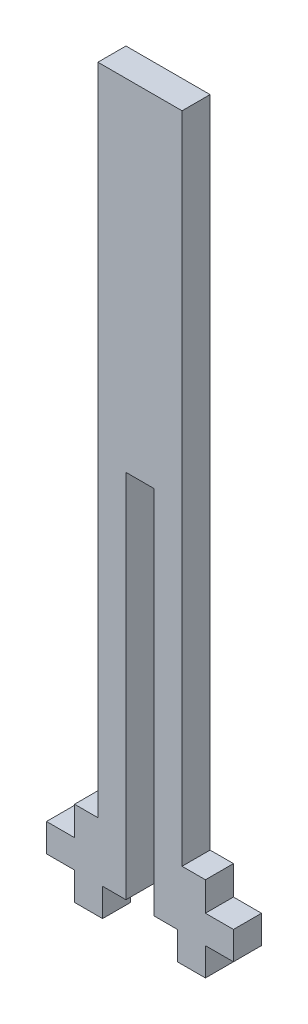
SolidWorks part; units mm, degrees
material "Plain Carbon Steel"
ref_plane "Front Plane" through (0, 0, 0) normal (0, 0, 1) x (1, 0, 0)
ref_plane "Top Plane" through (0, 0, 0) normal (0, 1, 0) x (1, 0, 0)
ref_plane "Right Plane" through (0, 0, 0) normal (1, 0, 0) x (0, 0, -1)
sketch "스케치1" plane through (0, 0, 0) normal (0, 0, 1) x (1, 0, 0)
  line L0 (0, 0) -> (0, -33.444) construction
  line L1 (-7, -39.544) -> (7, -39.544) construction
  line L2 (-7, -39.544) -> (-7, 39.544) construction
  line L3 (-7, 39.544) -> (7, 39.544) construction
  line L4 (7, -39.544) -> (7, 39.544) construction
  line L5 (-7, -39.544) -> (7, 39.544) construction
  line L6 (-7, 39.544) -> (7, -39.544) construction
  line L7 (-4, -39.544) -> (4, -39.544) construction
  line L8 (-4, -39.544) -> (-4, -33.444)
  line L9 (-4, -33.444) -> (4, -33.444)
  line L10 (4, -39.544) -> (4, -33.444)
  line L11 (-4, -39.544) -> (4, -33.444) construction
  line L12 (-4, -33.444) -> (4, -39.544) construction
  line L13 (4.5, -30.444) -> (-4.5, -30.444) construction
  line L14 (7, -30.444) -> (4.5, -30.444)
  line L15 (7, -30.444) -> (7, 39.544) construction
  line L16 (7, 39.544) -> (4.5, 39.544) construction
  line L17 (4.5, -30.444) -> (4.5, 39.544) construction
  line L18 (7, -30.444) -> (4.5, 39.544) construction
  line L19 (7, 39.544) -> (4.5, -30.444) construction
  line L20 (-4.5, 39.544) -> (-7, 39.544) construction
  line L21 (-4.5, 39.544) -> (-4.5, -30.444) construction
  line L22 (-4.5, -30.444) -> (-7, -30.444)
  line L23 (-7, 39.544) -> (-7, -30.444) construction
  line L24 (-4.5, 39.544) -> (-7, -30.444) construction
  line L25 (-4.5, -30.444) -> (-7, 39.544) construction
  line L26 (4, -39.544) -> (7, -39.544)
  line L27 (-1.5, 30.444) -> (1.5, 30.444) construction
  line L28 (-1.5, 30.444) -> (-1.5, -30.444) construction
  line L29 (-1.5, -30.444) -> (1.5, -30.444) construction
  line L30 (1.5, 30.444) -> (1.5, -30.444) construction
  line L31 (-1.5, 30.444) -> (1.5, -30.444) construction
  line L32 (-1.5, -30.444) -> (1.5, 30.444) construction
  line L33 (7, -39.544) -> (7, -30.444)
  line L34 (-7, -30.444) -> (-7, -39.544)
  line L35 (-7, -39.544) -> (-4, -39.544)
  line L36 (-4.5, 39.544) -> (-7, 39.544) construction
  line L37 (-7, 39.544) -> (-7, -39.544)
  line L38 (4.5, 39.544) -> (7, 39.544) construction
  line L39 (-4.5, -30.444) -> (-4.5, 39.544)
  line L40 (4.5, 39.544) -> (4.5, -30.444)
  line L41 (-4.5, 39.544) -> (4.5, 39.544)
  point P0 (0, 0)
  point P10 (0, -36.494)
  point P16 (5.75, 4.55)
  point P20 (-5.75, 4.55)
  dimension "D1" = 69.988
  dimension "D2" = 3
  dimension "D3" = 8
  dimension "D4" = 6.1
  dimension "D5" = 3
  dimension "D6" = 3
  dimension "D7" = 3
extrude "보스-돌출1" add sketch "스케치1" along normal blind 3 contours L41 L39 L22 L34 L35 L8 L9 L10 L26 L33 L14 L40
sketch "스케치2" plane through (0, 0, 0) normal (0, 0, -1) x (-1, 0, 0)
  line L0 (0, 39.544) -> (0, -33.444) construction
  line L1 (4.5, 39.544) -> (-4.5, 39.544) construction
  line L2 (4, -33.444) -> (-4, -33.444) construction
  line L4 (-1.5, -33.444) -> (1.5, -33.444)
  line L5 (-1.5, -33.444) -> (-1.5, 3.05)
  line L6 (-1.5, 3.05) -> (1.5, 3.05)
  line L7 (1.5, -33.444) -> (1.5, 3.05)
  line L8 (-1.5, -33.444) -> (1.5, 3.05) construction
  line L9 (-1.5, 3.05) -> (1.5, -33.444) construction
  point P6 (0, -15.197)
  point P11 (0, 3.05)
  dimension "D1" = 3
extrude "컷-돌출1" cut sketch "스케치2" against normal up to surface (3 mm away) up to face at (0, -22.3127, 3)
sketch "스케치3" plane through (0, 0, 3) normal (0, 0, 1) x (1, 0, 0)
  line L0 (-7, -30.444) -> (-7, -39.544) construction
  line L1 (-7, -33.544) -> (-10, -33.544)
  line L2 (-7, -33.544) -> (-7, -36.544)
  line L3 (-7, -36.544) -> (-10, -36.544)
  line L4 (-10, -33.544) -> (-10, -36.544)
  line L5 (-7, -33.544) -> (-10, -36.544) construction
  line L6 (-7, -36.544) -> (-10, -33.544) construction
  line L7 (7, -39.544) -> (7, -30.444) construction
  line L8 (7, -33.544) -> (10, -33.544)
  line L9 (7, -33.544) -> (7, -36.544)
  line L10 (7, -36.544) -> (10, -36.544)
  line L11 (10, -33.544) -> (10, -36.544)
  line L12 (7, -33.544) -> (10, -36.544) construction
  line L13 (7, -36.544) -> (10, -33.544) construction
  line L14 (-7, -39.544) -> (-4, -39.544) construction
  line L15 (4, -39.544) -> (7, -39.544) construction
  point P4 (-8.5, -35.044)
  point P11 (8.5, -35.044)
  dimension "D1" = 3
  dimension "D2" = 3
  dimension "D3" = 3
  dimension "D4" = 3
  dimension "D5" = 3
  dimension "D6" = 3
extrude "보스-돌출2" add sketch "스케치3" against normal blind 3
sketch "스케치5" plane through (0, 0, 3) normal (0, 0, 1) x (1, 0, 0)
  line L0 (4, -39.544) -> (4, -33.444) construction
  line L1 (-4, -33.444) -> (-1.5, -33.444)
  line L2 (-4, -33.444) -> (-4, -36.544)
  line L3 (-4, -36.544) -> (-1.5, -36.544)
  line L4 (-1.5, -33.444) -> (-1.5, -36.544)
  line L5 (-4, -33.444) -> (-1.5, -36.544) construction
  line L6 (-4, -36.544) -> (-1.5, -33.444) construction
  line L7 (1.5, -33.444) -> (4, -33.444)
  line L8 (1.5, -33.444) -> (1.5, -36.544)
  line L9 (1.5, -36.544) -> (4, -36.544)
  line L10 (4, -33.444) -> (4, -36.544)
  line L11 (1.5, -33.444) -> (4, -36.544) construction
  line L12 (1.5, -36.544) -> (4, -33.444) construction
  line L13 (-4, -36.544) -> (-7, -36.544) construction
  line L14 (4, -36.544) -> (7, -36.544) construction
  line L15 (-1.5, -33.444) -> (-1.5, 3.05) construction
  point P4 (-2.75, -34.994)
  point P10 (2.75, -34.994)
  point P15 (0, 0)
extrude "보스-돌출3" add sketch "스케치5" against normal blind 3
